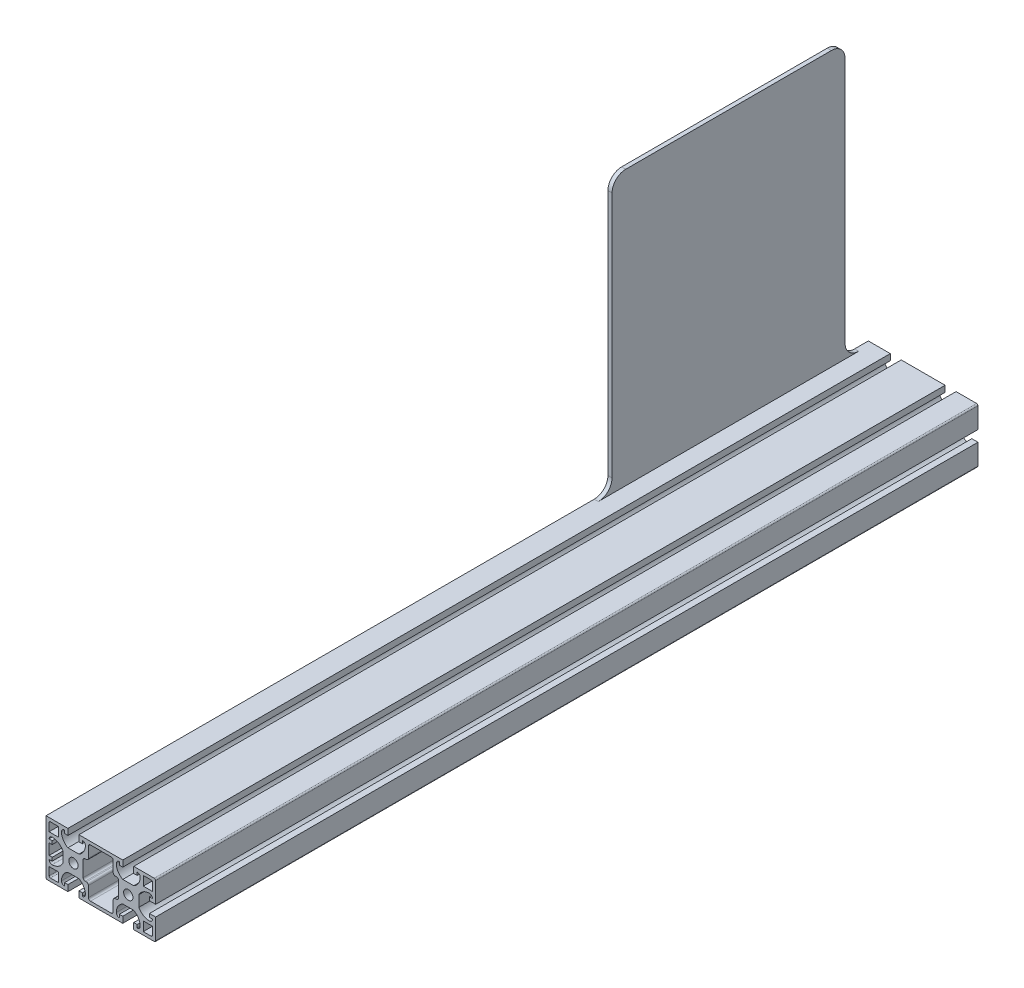
SolidWorks part; units mm, degrees
material "3.0255 (EN-AW 1350A)"
ref_plane "Płaszczyzna przednia" through (0, 0, 0) normal (0, 0, 1) x (1, 0, 0)
ref_plane "Płaszczyzna górna" through (0, 0, 0) normal (0, 1, 0) x (1, 0, 0)
ref_plane "Płaszczyzna prawa" through (0, 0, 0) normal (1, 0, 0) x (0, 0, -1)
sketch "Szkic1" plane through (0, 0, 0) normal (0, 0, 1) x (1, 0, 0)
  line L0 (0, 20) -> (0, -20) construction
  line L1 (-51.8865, 0) -> (40, 0) construction
  line L4 (-40, -19) -> (-40, 20)
  line L7 (-40, -20) -> (0, 0) construction
  line L8 (-40, 20) -> (40, -20) construction
  line L13 (20, 20) -> (20, 0) construction
  line L15 (24, 20) -> (24, 15.5)
  line L16 (24, 15.5) -> (26.4714, 15.5)
  line L21 (16, 15.5) -> (13.5286, 15.5)
  line L23 (16, 20) -> (13.5286, 20)
  line L24 (16, 20) -> (16, 15.5)
  line L25 (16, 7.75) -> (24, 7.75)
  line L26 (13.5286, 15.5) -> (13.5286, 17.75)
  line L27 (26.4714, 15.5) -> (26.4714, 17.75)
  line L28 (-24, 20) -> (-24, 15.5)
  line L29 (-26.4714, 15.5) -> (-26.4714, 17.75)
  line L30 (-24, 15.5) -> (-26.4714, 15.5)
  line L31 (-13.5286, 15.5) -> (-13.5286, 17.75)
  line L32 (-16, 15.5) -> (-13.5286, 15.5)
  line L33 (-16, 20) -> (-16, 15.5)
  line L34 (-16, 7.75) -> (-24, 7.75)
  line L35 (20, -20) -> (20, 0) construction
  line L36 (-40, -20) -> (0, 0) construction
  line L37 (-40, 20) -> (40, -20) construction
  line L38 (30.9714, -17.75) -> (36.75, -17.75)
  line L39 (-16, -7.75) -> (-24, -7.75)
  line L40 (-16, -20) -> (-16, -15.5)
  line L41 (-16, -15.5) -> (-13.5286, -15.5)
  line L42 (-13.5286, -15.5) -> (-13.5286, -17.75)
  line L43 (-24, -15.5) -> (-26.4714, -15.5)
  line L44 (-26.4714, -15.5) -> (-26.4714, -17.75)
  line L45 (-24, -20) -> (-24, -15.5)
  line L46 (26.4714, -15.5) -> (26.4714, -17.75)
  line L47 (13.5286, -15.5) -> (13.5286, -17.75)
  line L48 (16, -7.75) -> (24, -7.75)
  line L49 (16, -20) -> (16, -15.5)
  line L50 (16, -15.5) -> (13.5286, -15.5)
  line L51 (24, -15.5) -> (26.4714, -15.5)
  line L52 (24, -20) -> (24, -15.5)
  line L53 (40, -20) -> (0, 20) construction
  line L54 (35.5, 6.4714) -> (37.75, 6.4714)
  line L55 (35.5, 4) -> (35.5, 6.4714)
  line L56 (40, 4) -> (35.5, 4)
  line L57 (40, -4) -> (35.5, -4)
  line L58 (35.5, -4) -> (35.5, -6.4714)
  line L59 (35.5, -6.4714) -> (37.75, -6.4714)
  line L60 (27.75, 4) -> (27.75, -4)
  line L61 (-35.5, -6.4714) -> (-37.75, -6.4714)
  line L62 (-37.75, -4) -> (-35.5, -4)
  line L63 (-35.5, -4) -> (-35.5, -6.4714)
  line L64 (-35.5, 4) -> (-35.5, 6.4714)
  line L65 (-35.5, 6.4714) -> (-37.75, 6.4714)
  line L66 (-37.75, 4) -> (-35.5, 4)
  line L67 (-27.75, 4) -> (-27.75, -4)
  line L68 (-37.75, 4) -> (-37.75, -4)
  line L69 (40, -4) -> (40, -19)
  line L70 (40, 19) -> (40, 4)
  line L71 (-39, -20) -> (-24, -20)
  line L72 (-16, -20) -> (16, -20)
  line L73 (24, -20) -> (39, -20)
  line L74 (13.5286, 20) -> (-16, 20)
  line L75 (-24, 20) -> (-40, 20)
  line L76 (24, 20) -> (39, 20)
  line L77 (10.5286, 7.0902) -> (11.4095, 7.0902)
  line L78 (-7.5286, -17.75) -> (7.5286, -17.75)
  line L79 (-9.0286, -16.25) -> (-9.0286, -8.5902)
  line L80 (-7.5286, 17.75) -> (7.5286, 17.75)
  line L81 (9.0286, -16.25) -> (9.0286, -8.5902)
  line L82 (-9.0286, -17.75) -> (9.0286, 17.75) construction
  line L83 (-9.0286, 17.75) -> (9.0286, -17.75) construction
  line L84 (-11.4095, -7.0902) -> (-10.5286, -7.0902)
  line L85 (-12.9095, -5.5902) -> (-12.9095, 5.5902)
  line L86 (-11.4095, 7.0902) -> (-10.5286, 7.0902)
  line L87 (12.9095, -5.5902) -> (12.9095, 5.5902)
  line L88 (-12.9095, -7.0902) -> (0, 0) construction
  line L89 (-12.9095, 7.0902) -> (12.9095, -7.0902) construction
  line L90 (-9.0286, 8.5902) -> (-9.0286, 16.25)
  line L91 (-9.0286, 4.5143) -> (-9.0286, 4.9587)
  line L92 (-9.0286, -4.9587) -> (-9.0286, -4.5143)
  line L93 (9.0286, 8.5902) -> (9.0286, 16.25)
  line L94 (10.5286, -7.0902) -> (11.4095, -7.0902)
  line L96 (0, 0) -> (12.9095, 7.0902) construction
  line L98 (37.75, -10.9714) -> (37.75, -16.75)
  line L99 (30.9714, 10.9714) -> (37.75, 10.9714)
  line L100 (30.9714, 10.9714) -> (30.9714, 17.75)
  line L101 (30.9714, 17.75) -> (36.75, 17.75)
  line L102 (37.75, 10.9714) -> (37.75, 16.75)
  line L103 (30.9714, 10.9714) -> (37.75, 17.75) construction
  line L104 (30.9714, 17.75) -> (37.75, 10.9714) construction
  line L105 (30.9714, -10.9714) -> (37.75, -10.9714)
  line L106 (30.9714, -10.9714) -> (30.9714, -17.75)
  line L107 (-30.9714, -10.9714) -> (-30.9714, -17.75)
  line L108 (-30.9714, -10.9714) -> (-37.75, -10.9714)
  line L109 (-37.75, -10.9714) -> (-37.75, -16.75)
  line L110 (-30.9714, -17.75) -> (-36.75, -17.75)
  line L111 (-30.9714, 17.75) -> (-36.75, 17.75)
  line L112 (-37.75, 10.9714) -> (-37.75, 16.75)
  line L113 (-30.9714, 10.9714) -> (-37.75, 10.9714)
  line L114 (-30.9714, 10.9714) -> (-30.9714, 17.75)
  circle A0 centre (-20, 0) radius 3.4
  circle A1 centre (20, 0) radius 3.4
  arc A2 (26.4714, 17.75) -> (28.7214, 15.5) centre (26.4714, 15.5) cw
  arc A3 (28.7214, 15.5) -> (24, 7.75) centre (20, 15.5) cw
  arc A4 (13.5286, 17.75) -> (11.2786, 15.5) centre (13.5286, 15.5) ccw
  arc A5 (11.2786, 15.5) -> (16, 7.75) centre (20, 15.5) ccw
  arc A6 (-26.4714, 17.75) -> (-28.7214, 15.5) centre (-26.4714, 15.5) ccw
  arc A7 (-13.5286, 17.75) -> (-11.2786, 15.5) centre (-13.5286, 15.5) cw
  arc A8 (-11.2786, 15.5) -> (-16, 7.75) centre (-20, 15.5) cw
  arc A9 (-28.7214, 15.5) -> (-24, 7.75) centre (-20, 15.5) ccw
  arc A10 (-28.7214, -15.5) -> (-24, -7.75) centre (-20, -15.5) cw
  arc A11 (-11.2786, -15.5) -> (-16, -7.75) centre (-20, -15.5) ccw
  arc A12 (-13.5286, -17.75) -> (-11.2786, -15.5) centre (-13.5286, -15.5) ccw
  arc A13 (-26.4714, -17.75) -> (-28.7214, -15.5) centre (-26.4714, -15.5) cw
  arc A14 (11.2786, -15.5) -> (16, -7.75) centre (20, -15.5) cw
  arc A15 (13.5286, -17.75) -> (11.2786, -15.5) centre (13.5286, -15.5) cw
  arc A16 (28.7214, -15.5) -> (24, -7.75) centre (20, -15.5) ccw
  arc A17 (26.4714, -17.75) -> (28.7214, -15.5) centre (26.4714, -15.5) ccw
  arc A18 (35.5, 8.7214) -> (27.75, 4) centre (35.5, 0) ccw
  arc A19 (37.75, 6.4714) -> (35.5, 8.7214) centre (35.5, 6.4714) ccw
  arc A20 (37.75, -6.4714) -> (35.5, -8.7214) centre (35.5, -6.4714) cw
  arc A21 (35.5, -8.7214) -> (27.75, -4) centre (35.5, 0) cw
  arc A22 (-35.5, -8.7214) -> (-27.75, -4) centre (-35.5, 0) ccw
  arc A23 (-37.75, -6.4714) -> (-35.5, -8.7214) centre (-35.5, -6.4714) ccw
  arc A24 (-37.75, 6.4714) -> (-35.5, 8.7214) centre (-35.5, 6.4714) cw
  arc A25 (-35.5, 8.7214) -> (-27.75, 4) centre (-35.5, 0) cw
  arc A26 (-10.5286, 7.0902) -> (-9.0286, 8.5902) centre (-10.5286, 8.5902) ccw
  arc A27 (-9.0286, -8.5902) -> (-10.5286, -7.0902) centre (-10.5286, -8.5902) ccw
  arc A28 (11.4095, -7.0902) -> (12.9095, -5.5902) centre (11.4095, -5.5902) ccw
  arc A29 (9.0286, -8.5902) -> (10.5286, -7.0902) centre (10.5286, -8.5902) cw
  arc A30 (7.5286, -17.75) -> (9.0286, -16.25) centre (7.5286, -16.25) ccw
  arc A31 (-7.5286, -17.75) -> (-9.0286, -16.25) centre (-7.5286, -16.25) cw
  arc A32 (-11.4095, -7.0902) -> (-12.9095, -5.5902) centre (-11.4095, -5.5902) cw
  arc A33 (-12.9095, 5.5902) -> (-11.4095, 7.0902) centre (-11.4095, 5.5902) cw
  arc A34 (-9.0286, 16.25) -> (-7.5286, 17.75) centre (-7.5286, 16.25) cw
  arc A35 (7.5286, 17.75) -> (9.0286, 16.25) centre (7.5286, 16.25) cw
  arc A36 (11.4095, 7.0902) -> (12.9095, 5.5902) centre (11.4095, 5.5902) cw
  arc A37 (10.5286, 7.0902) -> (9.0286, 8.5902) centre (10.5286, 8.5902) cw
  arc A39 (-39, -20) -> (-40, -19) centre (-39, -19) cw
  arc A40 (39, -20) -> (40, -19) centre (39, -19) ccw
  arc A41 (39, 20) -> (40, 19) centre (39, 19) cw
  arc A42 (36.75, 17.75) -> (37.75, 16.75) centre (36.75, 16.75) cw
  arc A43 (36.75, -17.75) -> (37.75, -16.75) centre (36.75, -16.75) ccw
  arc A44 (-36.75, -17.75) -> (-37.75, -16.75) centre (-36.75, -16.75) cw
  arc A45 (-36.75, 17.75) -> (-37.75, 16.75) centre (-36.75, 16.75) ccw
  point P5 (0, 0)
  point P17 (0, 0)
  point P30 (24, 17.75)
  point P108 (0, 0)
  point P124 (-9.0286, 7.0902)
  point P132 (9.0286, -7.0902)
  point P156 (9.0286, 7.0902)
  point P161 (40, 20)
  point P162 (34.3607, 14.3607)
  dimension "D4" = 6.8
  dimension "D5" = 12.25
  dimension "D9" = 11
  dimension "D11" = 1.5
  dimension "D12" = 1
  dimension "D16" = 1
  dimension "D1" = 80
  dimension "D2" = 40
  dimension "D3" = 40
  dimension "D6" = 2.25
  dimension "D7" = 8
  dimension "D8" = 4.5
  dimension "D10" = 14.1804
  dimension "D13" = 2.25
  dimension "D14" = 2.25
  dimension "D15" = 2.25
extrude "Dodanie-wyciągnięcie1" add sketch "Szkic1" along normal blind 600 contours A20 A21 L60 A18 A19 L54 L55 L56 L70 L76 L15 L16 L27 A2 A3 L25 A5 A4 L26 L21 L24 L23 L74 L33 L32 L31 A7 A8 L34 A9 A6 L29 L30 L28 L75 L4 L71 L45 L43 L44 A13 A10 L39 A11 A12 L42 L41 L40 L72 L49 L50
sketch "Szkic2" plane through (-40, 0, 0) normal (-1, 0, 0) x (0, 0, 1)
  line L1 (20, 20) -> (190, 20)
  line L2 (20, 20) -> (20, 220)
  line L3 (20, 220) -> (190, 220)
  line L4 (190, 20) -> (190, 220)
  line L5 (0, -19) -> (0, 20) construction
  line L6 (600, 20) -> (0, 20) construction
  dimension "D1" = 200
  dimension "D2" = 170
  dimension "D3" = 20
extrude "Dodanie-wyciągnięcie3" add sketch "Szkic2" against normal blind 3
fillet "Zaokrąglenie1" radius 10 4 edges at (-38.5, 20, 190) (-38.5, 20, 20) (-38.5, 220, 20) (-38.5, 220, 190)
